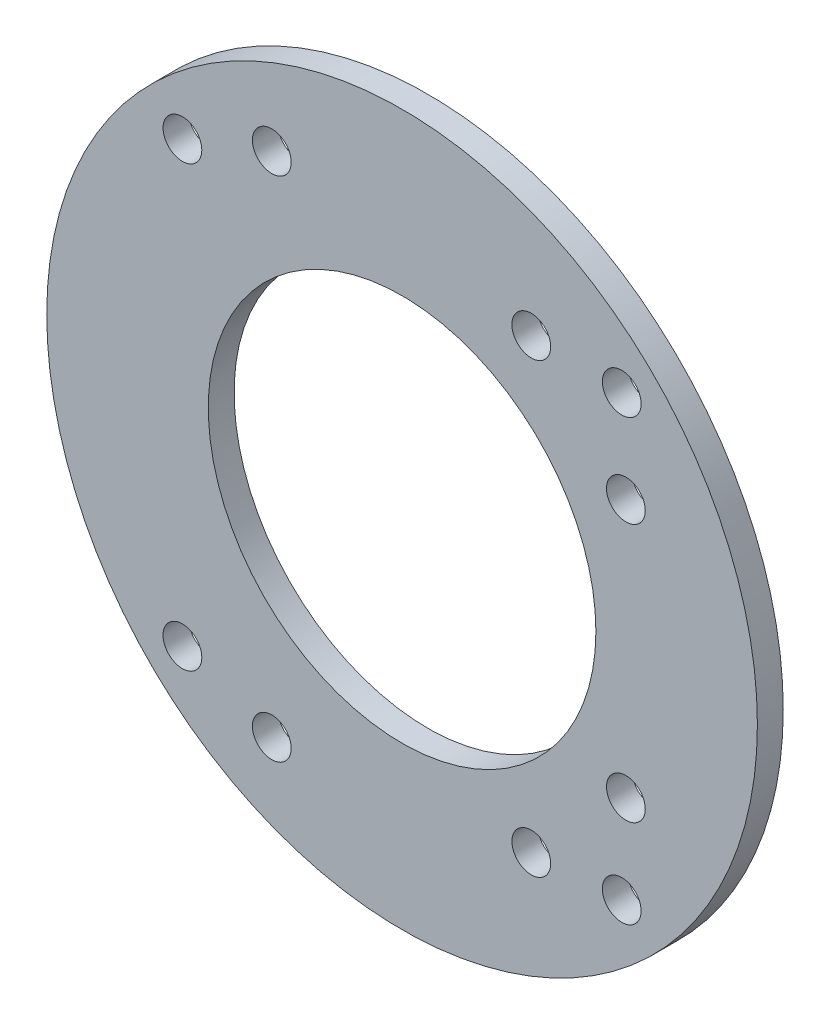
SolidWorks part; units mm, degrees
ref_plane "前视基准面" through (0, 0, 0) normal (0, 0, 1) x (1, 0, 0)
ref_plane "上视基准面" through (0, 0, 0) normal (0, 1, 0) x (1, 0, 0)
ref_plane "右视基准面" through (0, 0, 0) normal (1, 0, 0) x (0, 0, -1)
other "Configuration Table"
sketch "草图2" plane through (0, 0, 0) normal (0, 0, 1) x (1, 0, 0)
  line L0 (140, 0) -> (140, -21)
  line L1 (140, 0) -> (140, -17)
  line L2 (140, -17) -> (123, -17)
  line L3 (123, -17) -> (123, 17)
  line L4 (123, 17) -> (157, 17)
  line L5 (157, 17) -> (157, -17)
  line L6 (157, -17) -> (140, -17)
  circle A1 centre (140, 0) radius 27.5
  circle A2 centre (140, 0) radius 15
  circle A3 centre (157, -17) radius 1.5
  circle A4 centre (123, -17) radius 1.5
  circle A5 centre (123, 17) radius 1.5
  circle A6 centre (157, 17) radius 1.5
  circle A12 centre (150, 17.3205) radius 1.5
  circle A13 centre (129.9172, 19.6399) radius 1.5
  circle A15 centre (129.9172, -19.6399) radius 1.5
  circle A16 centre (150, -17.3205) radius 1.5
  circle A17 centre (157.3205, -10) radius 1.5
  circle A18 centre (157.3205, 10) radius 1.5
  dimension "D7" = 55
  dimension "D8" = 30
  dimension "D9" = 3
  dimension "D1" = 21
  dimension "D2" = 17
  dimension "D3" = 17
  dimension "D4" = 34
  dimension "D5" = 34
  dimension "D6" = 34
  dimension "D10" = 4
extrude "凸台-拉伸4" add sketch "草图2" along normal blind 2
